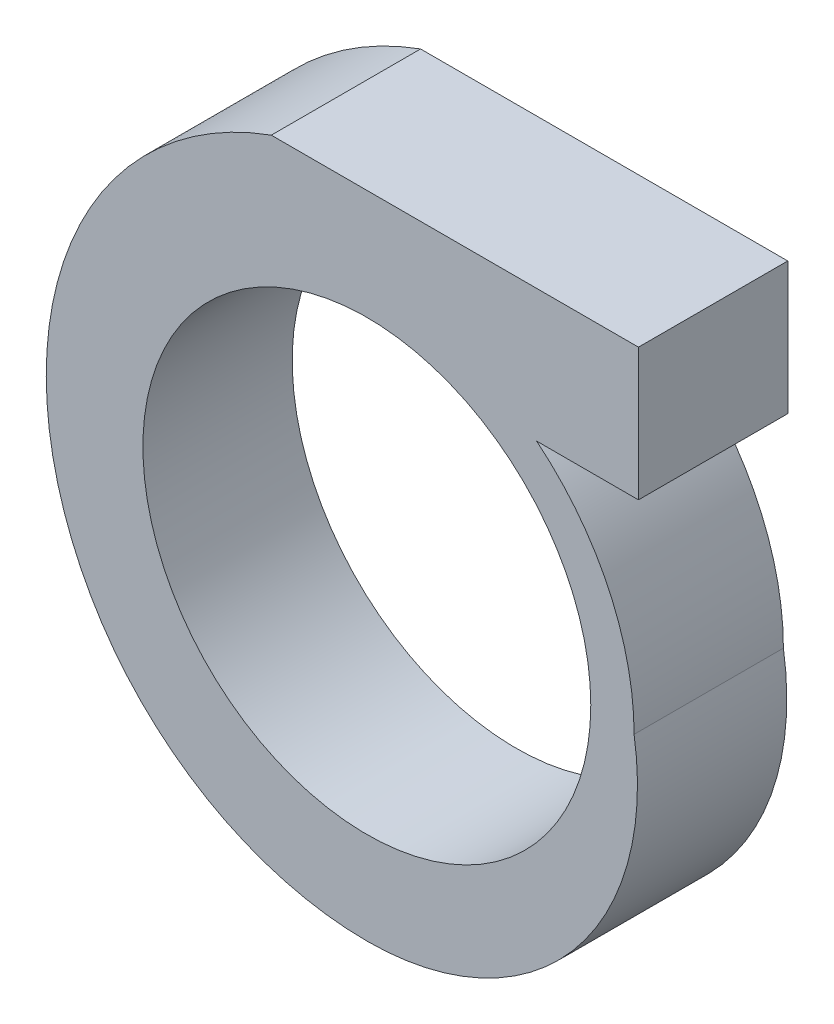
SolidWorks part; units mm, degrees
ref_plane "Front Plane" through (0, 0, 0) normal (0, 0, 1) x (1, 0, 0)
ref_plane "Top Plane" through (0, 0, 0) normal (0, 1, 0) x (1, 0, 0)
ref_plane "Right Plane" through (0, 0, 0) normal (1, 0, 0) x (0, 0, -1)
sketch "Sketch1" plane through (0, 0, 0) normal (0, 0, 1) x (1, 0, 0)
  line L0 (0, -59.9981) -> (0, 60.0019) construction
  line L1 (-0.1485, 0.9592) -> (-133.0605, -74.0428) construction
  line L2 (0, -59.9981) -> (0, -70.951) construction
  line L3 (0, -70.951) -> (-133.0605, -70.951) construction
  line L4 (-133.0605, -70.951) -> (-133.0605, -74.0428) construction
  line L5 (0, 60.0019) -> (0, 43.0728) construction
  line L6 (0, 43.0728) -> (-133.0605, 43.0728) construction
  line L7 (-133.0605, 43.0728) -> (-133.0605, -74.0428) construction
  line L8 (0, -70.951) -> (0, -83.7637) construction
  line L9 (0, -83.7637) -> (-133.0605, -83.7637) construction
  line L10 (-133.0605, -83.7637) -> (-133.0605, -70.951) construction
  line L11 (-25.753, 90.4266) -> (40.5052, 90.4266)
  line L16 (45.3415, 54.9909) -> (72.6248, 54.9909)
  line L17 (72.6248, 54.9909) -> (72.6248, 90.4266)
  line L18 (72.6248, 90.4266) -> (40.5052, 90.4266)
  circle A0 centre (-0.1485, 0.9592) radius 60
  circle A1 centre (0.5052, 0) radius 70.9528
  arc A2 (71.458, 0) -> (0, -83.7637) centre (0, -11.4018) cw
  arc A3 (0, -83.7637) -> (-74.0512, -40.744) centre (0, 1.4795) cw
  arc A4 (-74.0512, -40.744) -> (-25.753, 90.4266) centre (5.3148, 4.51) cw
  point P17 (-25.753, 90.4266)
  point P23 (0, 0)
  point P26 (0, -83.7637)
  point P27 (-74.0512, -40.744)
  dimension "D1" = 120
  dimension "D2" = 11.413
extrude "Boss-Extrude1" add sketch "Sketch1" along normal mid plane 40
